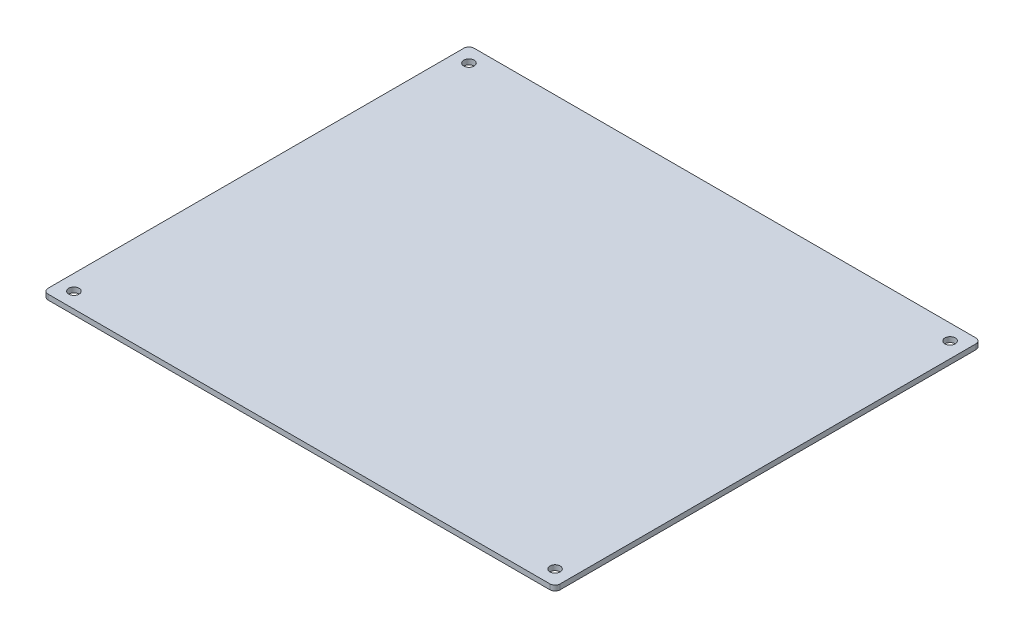
SolidWorks part; units mm, degrees
material "1060 Alloy"
ref_plane "Front Plane" through (0, 0, 0) normal (0, 0, 1) x (1, 0, 0)
ref_plane "Top Plane" through (0, 0, 0) normal (0, 1, 0) x (1, 0, 0)
ref_plane "Right Plane" through (0, 0, 0) normal (1, 0, 0) x (0, 0, -1)
sketch "Sketch1" plane through (0, 0, 0) normal (0, 1, 0) x (1, 0, 0)
  line L0 (148.735, 247.47) -> (148.735, 0) construction
  line L1 (0, 0) -> (297.47, 0)
  line L2 (0, 0) -> (0, 247.47)
  line L3 (0, 247.47) -> (297.47, 247.47)
  line L4 (297.47, 0) -> (297.47, 247.47)
  line L5 (148.735, 0) -> (297.47, 123.735) construction
  line L6 (297.47, 123.735) -> (0, 123.735) construction
  circle A0 centre (9, 238.47) radius 3
  circle A1 centre (288.47, 238.47) radius 3
  circle A2 centre (288.47, 9) radius 3
  circle A3 centre (9, 9) radius 3
  dimension "D3" = 6
  dimension "D5" = 9
  dimension "D1" = 247.47
  dimension "D2" = 297.47
  dimension "D4" = 9
extrude "Boss-Extrude1" add sketch "Sketch1" along normal blind 3
fillet "Fillet1" radius 3 4 edges at (297.47, 1.5, 0) (297.47, 1.5, -247.47) (0, 1.5, -247.47) (0, 1.5, 0)
